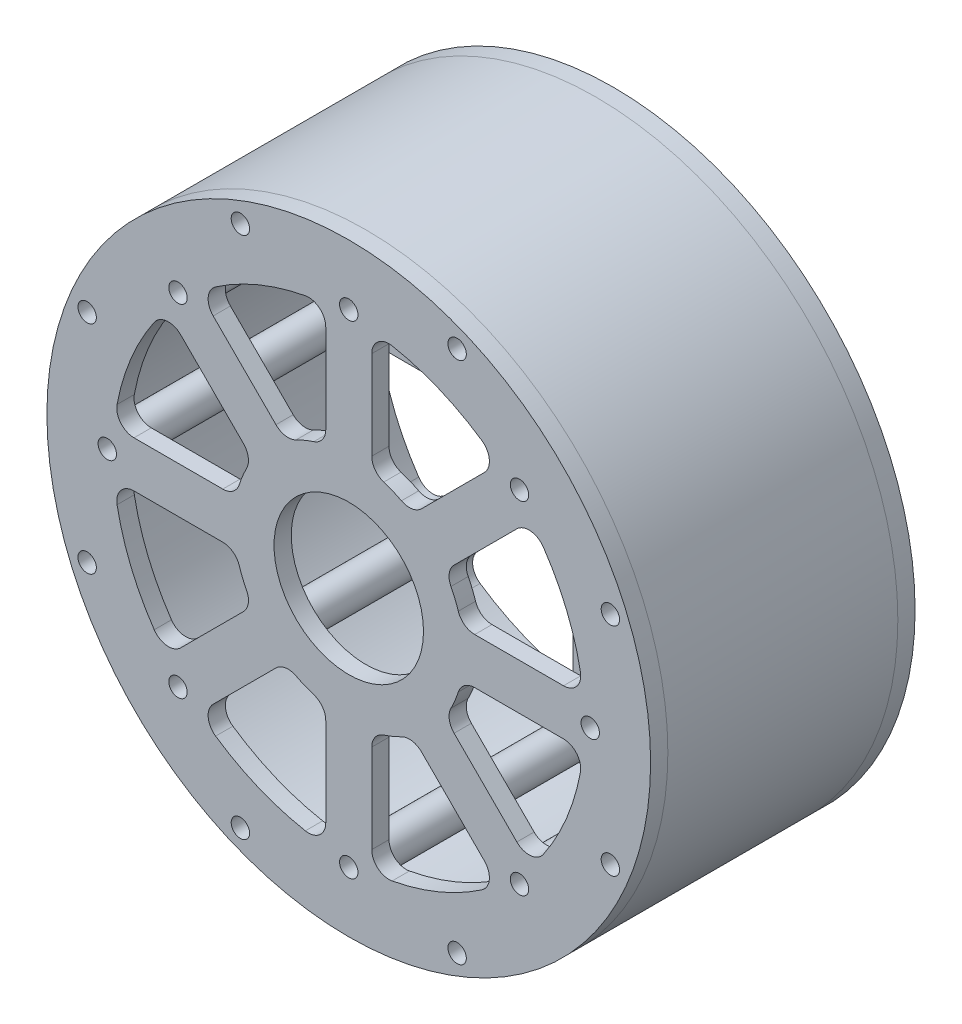
SolidWorks part; units mm, degrees
material "5052-H34"
ref_plane "正面" through (0, 0, 0) normal (0, 0, 1) x (1, 0, 0)
ref_plane "平面" through (0, 0, 0) normal (0, 1, 0) x (1, 0, 0)
ref_plane "右側面" through (0, 0, 0) normal (1, 0, 0) x (0, 0, -1)
sketch "ｽｹｯﾁ1" plane through (0, 0, 0) normal (0, 0, 1) x (1, 0, 0)
  line L0 (45.5011, 18.8472) -> (0, 0) construction
  line L1 (0, 0) -> (42, 0) construction
  line L2 (-4, 37.3497) -> (-4, 21.9089)
  line L3 (0, 42) -> (0, -42) construction
  line L4 (23.5818, 29.2387) -> (12.6635, 18.3204)
  line L5 (37.3497, 4) -> (21.9089, 4)
  line L6 (29.2387, -23.5818) -> (18.3204, -12.6635)
  line L7 (4, -37.3497) -> (4, -21.9089)
  line L8 (-23.5818, -29.2387) -> (-12.6635, -18.3204)
  line L9 (-37.3497, -4) -> (-21.9089, -4)
  line L10 (-29.2387, 23.5818) -> (-18.3204, 12.6635)
  line L12 (-12.6635, 18.3204) -> (-23.5818, 29.2387)
  line L14 (-21.9089, 4) -> (-37.3497, 4)
  line L16 (-18.3204, -12.6635) -> (-29.2387, -23.5818)
  line L18 (-4, -21.9089) -> (-4, -37.3497)
  line L20 (12.6635, -18.3204) -> (23.5818, -29.2387)
  line L22 (21.9089, -4) -> (37.3497, -4)
  line L24 (18.3204, 12.6635) -> (29.2387, 23.5818)
  line L26 (4, 21.9089) -> (4, 37.3497)
  circle A0 centre (0, 0) radius 42 construction
  circle A1 centre (0, 42) radius 3 construction
  circle A2 centre (29.6985, 29.6985) radius 3 construction
  circle A3 centre (42, 0) radius 3 construction
  circle A4 centre (29.6985, -29.6985) radius 3 construction
  circle A5 centre (0, -42) radius 3 construction
  circle A6 centre (-29.6985, -29.6985) radius 3 construction
  circle A7 centre (0, 0) radius 49.25 construction
  circle A8 centre (0, 0) radius 52.5
  circle A9 centre (-42, 0) radius 3 construction
  circle A10 centre (-29.6985, 29.6985) radius 3 construction
  arc A23 (-33.8358, 23.1547) -> (-40.2984, 7.5526) centre (0, 0) ccw
  circle A42 centre (29.6985, 29.6985) radius 1.6
  circle A43 centre (42, 0) radius 1.6
  circle A44 centre (29.6985, -29.6985) radius 1.6
  circle A45 centre (0, -42) radius 1.6
  circle A46 centre (-29.6985, -29.6985) radius 1.6
  circle A47 centre (-42, 0) radius 1.6
  circle A48 centre (-29.6985, 29.6985) radius 1.6
  circle A49 centre (0, 42) radius 1.6
  circle A50 centre (0, 0) radius 45 construction
  circle A51 centre (45.5011, 18.8472) radius 1.6
  circle A52 centre (45.5011, -18.8472) radius 1.6
  circle A53 centre (18.8472, -45.5011) radius 1.6
  circle A54 centre (-18.8472, -45.5011) radius 1.6
  circle A55 centre (-45.5011, -18.8472) radius 1.6
  circle A56 centre (-45.5011, 18.8472) radius 1.6
  circle A57 centre (-18.8472, 45.5011) radius 1.6
  circle A58 centre (18.8472, 45.5011) radius 1.6
  circle A65 centre (0, 0) radius 13
  arc A66 (-17.7754, 9.1671) -> (-19.0512, 6.087) centre (0, 0) ccw
  arc A67 (-40.2984, -7.5526) -> (-33.8358, -23.1547) centre (0, 0) ccw
  arc A68 (-23.1547, -33.8358) -> (-7.5526, -40.2984) centre (0, 0) ccw
  arc A69 (7.5526, -40.2984) -> (23.1547, -33.8358) centre (0, 0) ccw
  arc A70 (33.8358, -23.1547) -> (40.2984, -7.5526) centre (0, 0) ccw
  arc A71 (40.2984, 7.5526) -> (33.8358, 23.1547) centre (0, 0) ccw
  arc A72 (23.1547, 33.8358) -> (7.5526, 40.2984) centre (0, 0) ccw
  arc A73 (-7.5526, 40.2984) -> (-23.1547, 33.8358) centre (0, 0) ccw
  arc A74 (-6.087, 19.0512) -> (-9.1671, 17.7754) centre (0, 0) ccw
  arc A75 (9.1671, 17.7754) -> (6.087, 19.0512) centre (0, 0) ccw
  arc A76 (6.087, -19.0512) -> (9.1671, -17.7754) centre (0, 0) ccw
  arc A77 (-9.1671, -17.7754) -> (-6.087, -19.0512) centre (0, 0) ccw
  arc A78 (-19.0512, -6.087) -> (-17.7754, -9.1671) centre (0, 0) ccw
  arc A79 (17.7754, -9.1671) -> (19.0512, -6.087) centre (0, 0) ccw
  arc A80 (19.0512, 6.087) -> (17.7754, 9.1671) centre (0, 0) ccw
  arc A81 (4, 21.9089) -> (6.087, 19.0512) centre (7, 21.9089) ccw
  arc A82 (12.6635, 18.3204) -> (9.1671, 17.7754) centre (10.5422, 20.4417) cw
  arc A83 (18.3204, 12.6635) -> (17.7754, 9.1671) centre (20.4417, 10.5422) ccw
  arc A84 (21.9089, 4) -> (19.0512, 6.087) centre (21.9089, 7) cw
  arc A85 (21.9089, -4) -> (19.0512, -6.087) centre (21.9089, -7) ccw
  arc A86 (18.3204, -12.6635) -> (17.7754, -9.1671) centre (20.4417, -10.5422) cw
  arc A87 (12.6635, -18.3204) -> (9.1671, -17.7754) centre (10.5422, -20.4417) ccw
  arc A88 (4, -21.9089) -> (6.087, -19.0512) centre (7, -21.9089) cw
  arc A89 (-4, -21.9089) -> (-6.087, -19.0512) centre (-7, -21.9089) ccw
  arc A90 (-12.6635, -18.3204) -> (-9.1671, -17.7754) centre (-10.5422, -20.4417) cw
  arc A91 (-18.3204, -12.6635) -> (-17.7754, -9.1671) centre (-20.4417, -10.5422) ccw
  arc A92 (-21.9089, -4) -> (-19.0512, -6.087) centre (-21.9089, -7) cw
  arc A93 (-21.9089, 4) -> (-19.0512, 6.087) centre (-21.9089, 7) ccw
  arc A94 (-17.7754, 9.1671) -> (-18.3204, 12.6635) centre (-20.4417, 10.5422) ccw
  arc A95 (23.5818, -29.2387) -> (23.1547, -33.8358) centre (21.4605, -31.36) cw
  arc A96 (-29.2387, 23.5818) -> (-33.8358, 23.1547) centre (-31.36, 21.4605) ccw
  arc A97 (37.3497, -4) -> (40.2984, -7.5526) centre (37.3497, -7) cw
  arc A98 (-37.3497, -4) -> (-40.2984, -7.5526) centre (-37.3497, -7) ccw
  arc A99 (29.2387, 23.5818) -> (33.8358, 23.1547) centre (31.36, 21.4605) cw
  arc A100 (-23.5818, -29.2387) -> (-23.1547, -33.8358) centre (-21.4605, -31.36) ccw
  arc A101 (4, 37.3497) -> (7.5526, 40.2984) centre (7, 37.3497) cw
  arc A102 (4, -37.3497) -> (7.5526, -40.2984) centre (7, -37.3497) ccw
  arc A103 (-23.5818, 29.2387) -> (-23.1547, 33.8358) centre (-21.4605, 31.36) cw
  arc A104 (29.2387, -23.5818) -> (33.8358, -23.1547) centre (31.36, -21.4605) ccw
  arc A105 (-37.3497, 4) -> (-40.2984, 7.5526) centre (-37.3497, 7) cw
  arc A106 (37.3497, 4) -> (40.2984, 7.5526) centre (37.3497, 7) ccw
  arc A107 (-29.2387, -23.5818) -> (-33.8358, -23.1547) centre (-31.36, -21.4605) cw
  arc A108 (-4, -37.3497) -> (-7.5526, -40.2984) centre (-7, -37.3497) cw
  arc A109 (23.5818, 29.2387) -> (23.1547, 33.8358) centre (21.4605, 31.36) ccw
  arc A110 (-9.1671, 17.7754) -> (-12.6635, 18.3204) centre (-10.5422, 20.4417) cw
  arc A111 (-4, 37.3497) -> (-7.5526, 40.2984) centre (-7, 37.3497) ccw
  arc A112 (-4, 21.9089) -> (-6.087, 19.0512) centre (-7, 21.9089) cw
  point P17 (0, 0)
  point P41 (0, 0)
  point P48 (0, 0)
  point P52 (11.028, 16.6848)
  point P67 (19.5959, 4)
  point P70 (19.5959, -4)
  point P73 (16.6848, -11.028)
  point P76 (11.028, -16.6848)
  point P94 (0, 0)
  point P112 (0, 0)
  point P113 (4, -19.5959)
  point P136 (-11.028, -16.6848)
  point P141 (-19.5959, -4)
  point P174 (-4, -40.8044)
  point P179 (-11.028, 16.6848)
  point P182 (-4, 40.8044)
  point P185 (-4, 19.5959)
  dimension "D1" = 6
  dimension "D2" = 84
  dimension "D4" = 3.25
  dimension "D5" = 1
  dimension "D6" = 4
  dimension "D8" = 40
  dimension "D9" = 3.2
  dimension "D11" = 4.25
  dimension "D12" = 3.2
  dimension "D15" = 26
  dimension "D16" = 3
  dimension "D13" = 157.5
  dimension "D7" = 8
  dimension "D3" = 8
  dimension "D10" = 8
  dimension "D14" = 8
extrude "ﾎﾞｽ - 押し出し1" add sketch "ｽｹｯﾁ1" along normal blind 3
sketch "ｽｹｯﾁ4" plane through (0, 0, 3) normal (0, 0, 1) x (1, 0, 0)
  circle A0 centre (0, 0) radius 52.5
  circle A1 centre (0, 0) radius 49.5
  circle A3 centre (0, 0) radius 52.5 construction
  circle A4 centre (18.8472, 45.5011) radius 3
  dimension "D1" = 3
  dimension "D2" = 6
sketch "ｽｹｯﾁ5" plane through (0, 0, 3) normal (0, 0, 1) x (1, 0, 0)
  circle A0 centre (0, 0) radius 52.5
  circle A1 centre (0, 0) radius 52.5 construction
  circle A2 centre (0, 0) radius 46
  circle A3 centre (-45.5011, 18.8472) radius 1.6 construction
  circle A4 centre (-45.5011, -18.8472) radius 1.6 construction
  circle A5 centre (-18.8472, -45.5011) radius 1.6 construction
  circle A6 centre (18.8472, -45.5011) radius 1.6 construction
  circle A7 centre (45.5011, -18.8472) radius 1.6 construction
  circle A8 centre (45.5011, 18.8472) radius 1.6 construction
  circle A9 centre (18.8472, 45.5011) radius 1.6 construction
  circle A10 centre (-18.8472, 45.5011) radius 1.6 construction
  circle A11 centre (-45.5011, 18.8472) radius 1.6
  circle A12 centre (-45.5011, -18.8472) radius 1.6
  circle A13 centre (-18.8472, -45.5011) radius 1.6
  circle A14 centre (18.8472, -45.5011) radius 1.6
  circle A15 centre (45.5011, -18.8472) radius 1.6
  circle A16 centre (45.5011, 18.8472) radius 1.6
  circle A17 centre (18.8472, 45.5011) radius 1.6
  circle A18 centre (-18.8472, 45.5011) radius 1.6
  dimension "D1" = 6.5
extrude "ﾎﾞｽ - 押し出し3" add sketch "ｽｹｯﾁ5" along normal blind 40 separate body
ref_plane "平面1" through (0, 0, 23) normal (0, 0, 1) x (1, 0, 0)
sketch "ｽｹｯﾁ2" plane through (0, 0, 3) normal (0, 0, 1) x (1, 0, 0)
  circle A0 centre (0, 0) radius 42 construction
  circle A1 centre (0, 42) radius 3
  circle A2 centre (29.6985, 29.6985) radius 3
  circle A3 centre (42, 0) radius 3
  circle A4 centre (29.6985, -29.6985) radius 3
  circle A5 centre (0, -42) radius 3
  circle A6 centre (-29.6985, -29.6985) radius 3
  circle A7 centre (-42, 0) radius 3
  circle A8 centre (-29.6985, 29.6985) radius 3
  point P17 (0, 0)
  dimension "D1" = 84
  dimension "D2" = 6
  dimension "D3" = 8
extrude "ｶｯﾄ - 押し出し1" cut sketch "ｽｹｯﾁ2" against normal blind 0.5
mirror "ﾐﾗｰ1" about plane through (0, 0, 23) normal (0, 0, 1) of bodies 102
sketch "ｽｹｯﾁ3" plane through (0, 0, 2.5) normal (0, 0, 1) x (1, 0, 0)
  circle A1 centre (29.6985, 29.6985) radius 3 construction
  circle A2 centre (42, 0) radius 3 construction
  circle A3 centre (29.6985, -29.6985) radius 3 construction
  circle A4 centre (0, -42) radius 3 construction
  circle A5 centre (-29.6985, -29.6985) radius 3 construction
  circle A6 centre (0, 42) radius 3 construction
  circle A7 centre (29.6985, 29.6985) radius 3
  circle A8 centre (42, 0) radius 3
  circle A9 centre (29.6985, -29.6985) radius 3
  circle A10 centre (0, -42) radius 3
  circle A11 centre (-29.6985, -29.6985) radius 3
  circle A12 centre (0, 42) radius 3
  circle A13 centre (-42, 0) radius 3 construction
  circle A14 centre (-29.6985, 29.6985) radius 3 construction
  circle A15 centre (-42, 0) radius 3
  circle A16 centre (-29.6985, 29.6985) radius 3
extrude "ﾎﾞｽ - 押し出し2" add sketch "ｽｹｯﾁ3" along normal up to surface (41 mm away) separate body up to face at (1.6, -42, 43.5)
